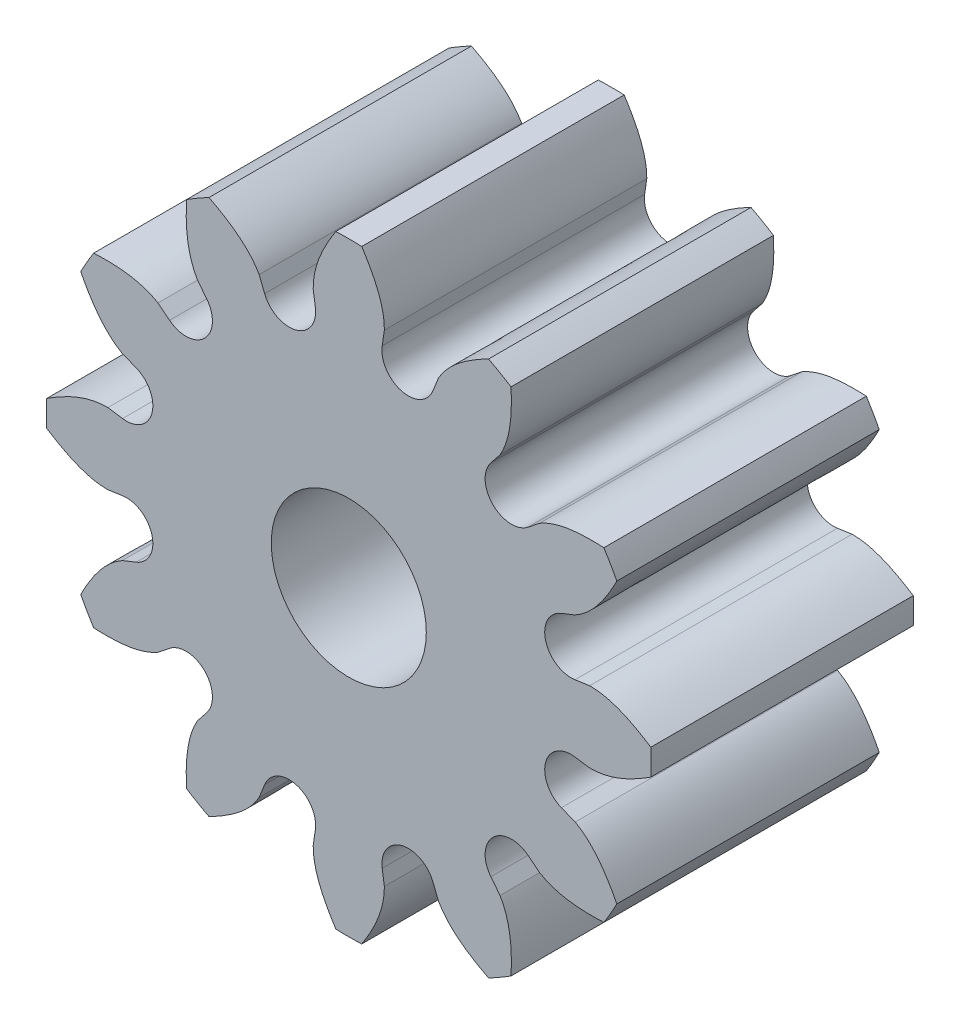
SolidWorks part; units mm, degrees
material "PE Low/Medium Density"
ref_plane "Front Plane" through (0, 0, 0) normal (0, 0, 1) x (1, 0, 0)
ref_plane "Top Plane" through (0, 0, 0) normal (0, 1, 0) x (1, 0, 0)
ref_plane "Right Plane" through (0, 0, 0) normal (1, 0, 0) x (0, 0, -1)
sketch "Involute construction sketch" plane through (0, 0, 0) normal (0, 0, 1) x (1, 0, 0)
  line L0 (0, 0) -> (-1.7439, 2.1811) construction
  line L1 (0, 0) -> (-1.0894, 2.5713) construction
  line L2 (0, 0) -> (-0.3538, 2.7701) construction
  line L3 (0, 0) -> (0.4081, 2.7626) construction
  line L4 (-2.6243, 0.9546) -> (-2.2686, 1.6285) construction
  line L5 (-2.2686, 1.6285) -> (-1.7439, 2.1811) construction
  line L6 (-1.7439, 2.1811) -> (-1.0894, 2.5713) construction
  line L7 (0, 0) -> (-2.2686, 1.6285) construction
  line L8 (0, 0) -> (-2.6243, 0.9546) construction
  line L9 (-1.0894, 2.5713) -> (-0.3538, 2.7701) construction
  line L10 (-0.3538, 2.7701) -> (0.4081, 2.7626) construction
  line L11 (-2.6243, 0.9546) -> (-1.3219, 4.5351) construction
  line L12 (-2.2686, 1.6285) -> (-0.4912, 4.1046) construction
  line L13 (-1.7439, 2.1811) -> (0.0415, 3.6087) construction
  line L14 (-1.0894, 2.5713) -> (0.3138, 3.1658) construction
  line L15 (-0.3538, 2.7701) -> (0.402, 2.8666) construction
  line L17 (0, 0) -> (0, 5.7859) construction
  line L18 (0, 0) -> (0.3879, 2.9464) construction
  line L19 (0, 0) -> (0.6048, 2.2572) construction
  circle A0 centre (0, 0) radius 2.3368 construction
  circle A1 centre (0, 0) radius 2.7926 construction
  circle A2 centre (0, 0) radius 2.9718 construction
  circle A3 centre (0, 0) radius 3.4671 construction
  spline S0 degree 3 poles (0.4081, 2.7626) (0.4101, 2.9021) (0.3192, 3.2075) (-0.15, 3.946) (-0.8068, 4.3472) (-1.3219, 4.5351) knots 0 0 0 0 0.160098 0.360084 1 1 1 1 construction
  point P17 (0.1486, 3.4639)
  dimension "D1" = 4.6736
  dimension "D2" = 5.5852
  dimension "D3" = 5.9436
  dimension "D4" = 6.9342
  dimension "D5" = 0.762
  dimension "D6" = 1.524
  dimension "D7" = 2.286
  dimension "D8" = 3.048
  dimension "D9" = 3.81
  dimension "D10" = 7.5
  dimension "D11" = 15
sketch "Sketch2" plane through (0, 0, 0) normal (0, 0, 1) x (1, 0, 0)
  line L0 (0, 3.4671) -> (0, 2.3368)
  line L1 (0, 0) -> (0, 5.7859) construction
  line L2 (0.4081, 2.7626) -> (0.3833, 2.5944)
  line L3 (0, 0) -> (0.4081, 2.7626) construction
  circle A0 centre (0, 0) radius 3.4671 construction
  circle A1 centre (0, 0) radius 2.3368 construction
  arc A2 (0, 3.4671) -> (0.1486, 3.4639) centre (0, 0) cw
  arc A3 (0, 2.3368) -> (0.6048, 2.2572) centre (0, 0) cw
  arc A4 (0.3833, 2.5944) -> (0.6048, 2.2572) centre (0.6833, 2.5501) ccw
  spline S0 degree 3 poles (0.4081, 2.7626) (0.4091, 2.8245) (0.3774, 3.0766) (0.25, 3.3056) (0.1486, 3.4639) knots 0 0 0 0 0.244448 1 1 1 1
sketch "Sketch3" plane through (0, 0, 0) normal (0, 0, 1) x (1, 0, 0)
  circle A0 centre (0, 0) radius 2.3368
  circle A1 centre (0, 0) radius 0.889
  dimension "D1" = 4.6736
  dimension "D2" = 1.778
extrude "Base" add sketch "Sketch3" along normal blind 3.0099
extrude "Half tooth" add sketch "Sketch2" along normal up to surface (3.0099 mm away) up to face at (2.3368, 0, 3.0099)
ref_plane "Midplane of half tooth" through (0, 0, 0) normal (-1, 0, 0) x (0, 0, 1)
mirror "Mirror of half tooth" about plane through (0, 0, 0) normal (-1, 0, 0) of "Half tooth"
pattern_circular "Pattern of half tooth" count 12 over 360 of "Half tooth", "Mirror of half tooth"
equation "\"radtodeg\"= 180 / PI'radian to degree conversion [ ]"
equation "\"phi\"= 20'pressure angle [deg]"
equation "\"N\"= 12'number of teeth [teeth]"
equation "\"A\"= 0.273in'diameter of addendum circle [inch]"
equation "\"B\"= 0.184in'diameter of dedendum circle [inch]"
equation "\"P\"= ( \"N\" + 2 ) / \"A\"'diametral pitch [teeth/inch]"
equation "\"d\"= \"N\" / \"P\"'diameter of pitch circle [inch]"
equation "\"cp\"= PI / \"P\"'circular pitch [inch/teeth]"
equation "\"add\"= 1 / \"P\"'addendum [inch]"
equation "\"ded\"= - ( \"B\" - \"d\" ) / 2'dedendum [inch]"
equation "\"clear\"= \"ded\" - \"add\"'clearance [inch]"
equation "\"C\"= \"B\" + 2 * \"clear\"'diameter of clearance circle [inch]"
equation "\"h\"= \"add\" + \"ded\"'tooth height / whole depth [inch]"
equation "\"s\"= \"d\" * cos ( \"phi\" * 1 / \"radtodeg\" )'diameter of base circle [inch]"
equation "\"t\"= ( PI / 2 ) / \"P\"'tooth width at diameter of pitch circle diameter [inch]"
equation "\"alpha\"= ( \"t\" / ( \"d\" / 2 ) * \"radtodeg\" ) / 2'arc angle for half of tooth width at pitch circle diameter [inch]"
equation "\"bore\"= 0.07'bore of hub [inch]"
equation "\"D4@Involute construction sketch\"= \"A\"'addendum circle"
equation "\"D3@Involute construction sketch\"= \"d\"'pitch circle"
equation "\"D2@Involute construction sketch\"= \"s\"'base circle"
equation "\"D1@Involute construction sketch\"= \"B\"'dedendum circle"
equation "\"seg\"= \"D5@Involute construction sketch\"'size of one involute segment [inch]"
equation "\"D6@Involute construction sketch\"=2*\"seg\""
equation "\"D7@Involute construction sketch\"=3*\"seg\""
equation "\"D8@Involute construction sketch\"=4*\"seg\""
equation "\"D9@Involute construction sketch\"=5*\"seg\""
equation "\"D10@Involute construction sketch\"=\"alpha\""
equation "\"D11@Involute construction sketch\"=2*\"alpha\""
equation "\"D1@Sketch3\"=\"B\""
equation "\"D2@Sketch3\"=\"bore\""
